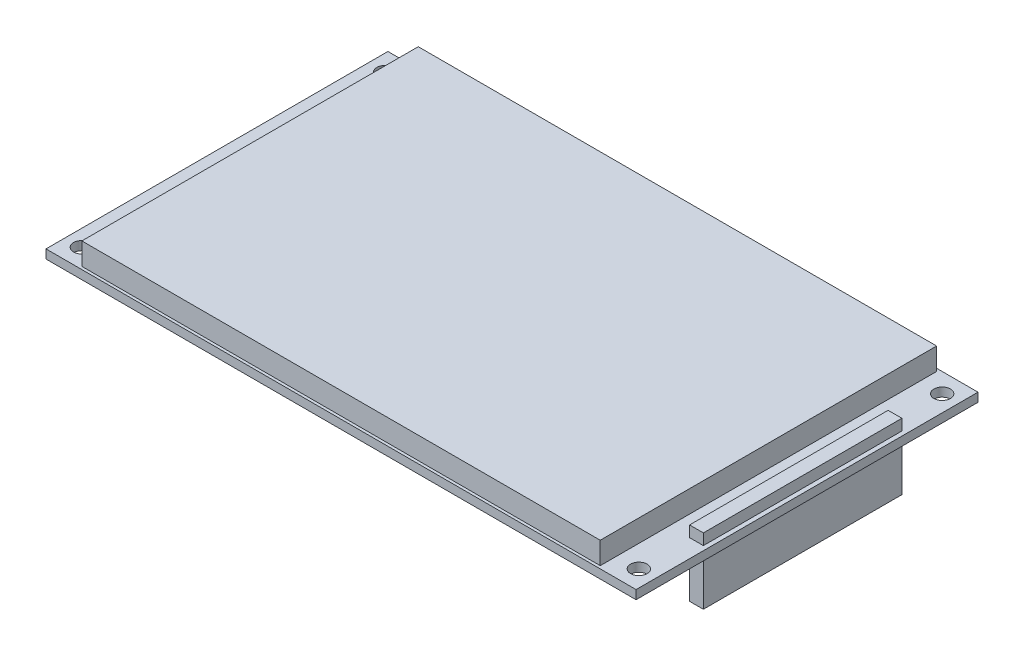
SolidWorks part; units mm, degrees
ref_plane "Piano frontale" through (0, 0, 0) normal (0, 0, 1) x (1, 0, 0)
ref_plane "Piano superiore" through (0, 0, 0) normal (0, 1, 0) x (1, 0, 0)
ref_plane "Piano destro" through (0, 0, 0) normal (1, 0, 0) x (0, 0, -1)
sketch "Schizzo1" plane through (0, 0, 0) normal (0, 1, 0) x (1, 0, 0)
  line L1 (-47, -30.5) -> (47, -30.5)
  line L2 (-47, -30.5) -> (-47, 30.5)
  line L3 (-47, 30.5) -> (47, 30.5)
  line L4 (47, -30.5) -> (47, 30.5)
  dimension "D1" = 30.5
  dimension "D2" = 47
  dimension "D3" = 94
  dimension "D4" = 61
extrude "Estrusione-Estrusione1" add sketch "Schizzo1" along normal blind 4
sketch "Schizzo2" plane through (0, 0, 0) normal (0, -1, 0) x (1, 0, 0)
  line L0 (-47, -30.5) -> (-47, 30.5) construction
  line L1 (-53, -31) -> (54, -31)
  line L2 (-53, -31) -> (-53, 31)
  line L3 (-53, 31) -> (54, 31)
  line L4 (54, -31) -> (54, 31)
  line L5 (47, 30.5) -> (47, -30.5) construction
  line L6 (-47, 30.5) -> (47, 30.5) construction
  line L7 (47, -30.5) -> (-47, -30.5) construction
  dimension "D1" = 6
  dimension "D2" = 7
  dimension "D3" = 0.5
  dimension "D4" = 0.5
extrude "Estrusione-Estrusione2" add sketch "Schizzo2" along normal blind 1.6
sketch "Schizzo4" plane through (0, 0, 0) normal (0, 1, 0) x (1, 0, 0)
  line L1 (53.2, 18) -> (50.7, 18)
  line L2 (53.2, 18) -> (53.2, -18)
  line L3 (53.2, -18) -> (50.7, -18)
  line L4 (50.7, 18) -> (50.7, -18)
  line L6 (54, 31) -> (54, -31) construction
  line L7 (54, -31) -> (-53, -31) construction
  dimension "D1" = 36
  dimension "D2" = 2.5
  dimension "D3" = 0.8
  dimension "D4" = 13
extrude "Estrusione-Estrusione3" add sketch "Schizzo4" along normal blind 2 and the other way blind 10
sketch "Schizzo6" plane through (0, 0, 0) normal (0, 1, 0) x (1, 0, 0)
  line L0 (-53, 31) -> (54, 31) construction
  line L1 (54, -31) -> (-53, -31) construction
  line L3 (-53, -31) -> (-53, 31) construction
  line L4 (54, 31) -> (54, -31) construction
  circle A0 centre (-50, 27.5) radius 1.5
  circle A1 centre (-50, -27.5) radius 1.5
  circle A2 centre (51, 27.5) radius 1.5
  circle A3 centre (51, -27.5) radius 1.5
  dimension "D1" = 3
  dimension "D2" = 3
  dimension "D3" = 3
  dimension "D4" = 3
  dimension "D9" = 3
  dimension "D10" = 3
  dimension "D11" = 3
  dimension "D12" = 3
  dimension "D5" = 3.5
  dimension "D6" = 3.5
  dimension "D7" = 3.5
  dimension "D8" = 3.5
extrude "Taglio-Estrusione1" cut sketch "Schizzo6" against normal blind 2
sketch "Schizzo7" plane through (0, -1.6, 0) normal (0, -1, 0) x (1, 0, 0)
  line L1 (-25, 9.5) -> (2, 9.5)
  line L2 (-25, 9.5) -> (-25, 26.5)
  line L3 (-25, 26.5) -> (2, 26.5)
  line L4 (2, 9.5) -> (2, 26.5)
  line L5 (54, 31) -> (-53, 31) construction
  line L6 (-53, 31) -> (-53, -31) construction
  dimension "D1" = 4.5
  dimension "D2" = 17
  dimension "D3" = 27
  dimension "D4" = 28
extrude "Estrusione-Estrusione4" add sketch "Schizzo7" along normal blind 3 contours L3 L4 L1 L2
